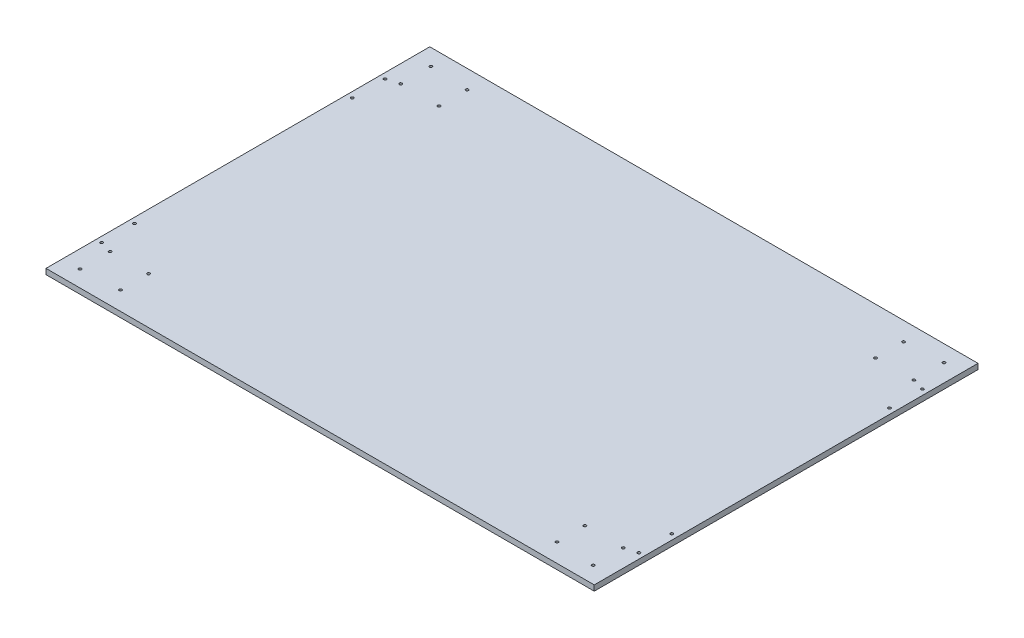
SolidWorks part; units mm, degrees
ref_plane "Front Plane" through (0, 0, 0) normal (0, 0, 1) x (1, 0, 0)
ref_plane "Top Plane" through (0, 0, 0) normal (0, 1, 0) x (1, 0, 0)
ref_plane "Right Plane" through (0, 0, 0) normal (1, 0, 0) x (0, 0, -1)
sketch "Sketch1" plane through (0, 0, 0) normal (0, 1, 0) x (1, 0, 0)
  line L1 (-635, 444.5) -> (635, 444.5)
  line L2 (-635, 444.5) -> (-635, -444.5)
  line L3 (-635, -444.5) -> (635, -444.5)
  line L4 (635, 444.5) -> (635, -444.5)
  line L5 (-635, 444.5) -> (635, -444.5) construction
  line L6 (-635, -444.5) -> (635, 444.5) construction
  point P0 (0, 0)
  dimension "D1" = 1270
  dimension "D2" = 889
extrude "Boss-Extrude1" add sketch "Sketch1" along normal blind 12.7
sketch "Sketch3" plane through (0, 12.7, 0) normal (0, 1, 0) x (1, 0, 0)
  line L0 (-635, 444.5) -> (-635, -444.5) construction
  line L1 (635, 444.5) -> (-635, 444.5) construction
  circle A0 centre (-594.36, 406.4) radius 3.175
  circle A1 centre (-505.601, 401.3943) radius 3.175
  circle A2 centre (-594.36, 336.55) radius 3.175
  circle A5 centre (-505.46, 336.55) radius 3.175
  circle A6 centre (505.601, 401.3943) radius 3.175
  circle A7 centre (505.46, 336.55) radius 3.175
  circle A8 centre (594.36, 336.55) radius 3.175
  circle A9 centre (594.36, 406.4) radius 3.175
  circle A10 centre (505.46, -336.55) radius 3.175
  circle A11 centre (505.601, -401.3943) radius 3.175
  circle A12 centre (594.36, -406.4) radius 3.175
  circle A13 centre (594.36, -336.55) radius 3.175
  circle A14 centre (-505.46, -336.55) radius 3.175
  circle A15 centre (-505.601, -401.3943) radius 3.175
  circle A16 centre (-594.36, -336.55) radius 3.175
  circle A17 centre (-594.36, -406.4) radius 3.175
  dimension "D1" = 40.64
  dimension "D4" = 69.85
  dimension "D2" = 38.1
extrude "Cut-Extrude4" cut sketch "Sketch3" against normal blind 12.192
sketch "Sketch4" plane through (0, 12.7, 0) normal (0, 1, 0) x (1, 0, 0)
  line L0 (0, 444.5) -> (0, -444.5) construction
  line L1 (635, 444.5) -> (-635, 444.5) construction
  line L2 (-635, -444.5) -> (635, -444.5) construction
  line L3 (-635, 0) -> (635, 0) construction
  line L4 (-635, 444.5) -> (-635, -444.5) construction
  line L5 (635, -444.5) -> (635, 444.5) construction
  line L6 (-622.3, 328.295) -> (-622.3, 252.095) construction
  circle A2 centre (-622.3, 328.295) radius 0.0385
  circle A3 centre (-622.3, 328.295) radius 3.175
  circle A4 centre (-622.3, 252.095) radius 3.175
  circle A5 centre (622.3, 252.095) radius 3.175
  circle A6 centre (622.3, 328.295) radius 3.175
  circle A7 centre (622.3, -252.095) radius 3.175
  circle A8 centre (622.3, -328.295) radius 3.175
  circle A9 centre (-622.3, -252.095) radius 3.175
  circle A10 centre (-622.3, -328.295) radius 3.175
  dimension "D2" = 12.7
  dimension "D1" = 76.2
extrude "Cut-Extrude6" cut sketch "Sketch4" against normal blind 445.516
